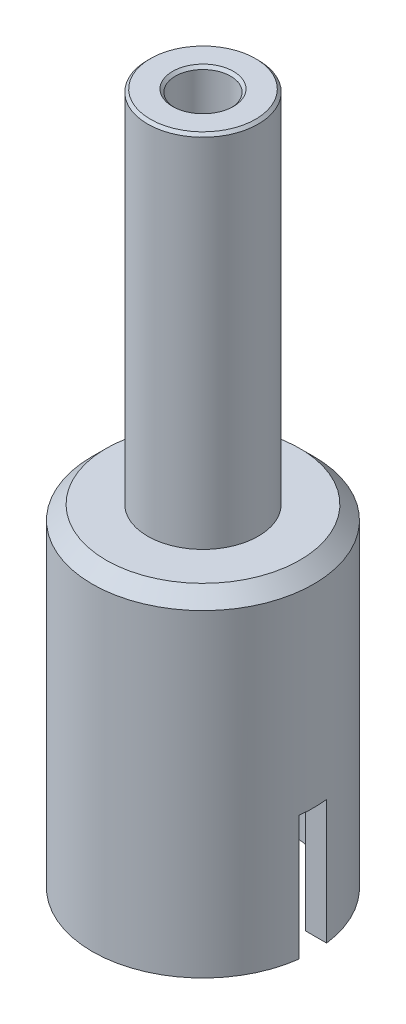
SolidWorks part; units mm, degrees
material "Lega 1345"
ref_plane "Piano frontale" through (0, 0, 0) normal (0, 0, 1) x (1, 0, 0)
ref_plane "Piano superiore" through (0, 0, 0) normal (0, 1, 0) x (1, 0, 0)
ref_plane "Piano destro" through (0, 0, 0) normal (1, 0, 0) x (0, 0, -1)
sketch "Schizzo1" plane through (0, 0, 0) normal (0, 1, 0) x (1, 0, 0)
  circle A0 centre (0, 0) radius 40
  dimension "D1" = 80
extrude "Estrusione1" add sketch "Schizzo1" along normal blind 120
sketch "Schizzo2" plane through (0, 0, 0) normal (0, -1, 0) x (1, 0, 0)
  circle A0 centre (0, 0) radius 32.5
  dimension "D1" = 65
extrude "Estrusione2" cut sketch "Schizzo2" against normal blind 110
chamfer "Smusso1" distance 5 angle 45 1 edges at (0, 120, 40)
sketch "Schizzo3" plane through (0, 120, 0) normal (0, 1, 0) x (1, 0, 0)
  circle A0 centre (0, 0) radius 20
  dimension "D1" = 40
extrude "Estrusione3" add sketch "Schizzo3" along normal blind 130
sketch "Schizzo4" plane through (0, 250, 0) normal (0, 1, 0) x (1, 0, 0)
  circle A0 centre (0, 0) radius 10
  dimension "D1" = 20
extrude "Estrusione4" cut sketch "Schizzo4" against normal through all
chamfer "Smusso2" distance 1 angle 45 2 edges at (0, 250, 10) (0, 250, 20)
sketch "Schizzo5" plane through (0, 0, 0) normal (0, -1, 0) x (1, 0, 0)
  line L1 (-44.1687, -5) -> (44.1687, -5)
  line L2 (-44.1687, -5) -> (-44.1687, 5)
  line L3 (-44.1687, 5) -> (44.1687, 5)
  line L4 (44.1687, -5) -> (44.1687, 5)
  line L5 (-44.1687, -5) -> (44.1687, 5) construction
  line L6 (-44.1687, 5) -> (44.1687, -5) construction
  point P0 (0, 0)
  dimension "D1" = 10
extrude "Estrusione5" cut sketch "Schizzo5" against normal blind 45
